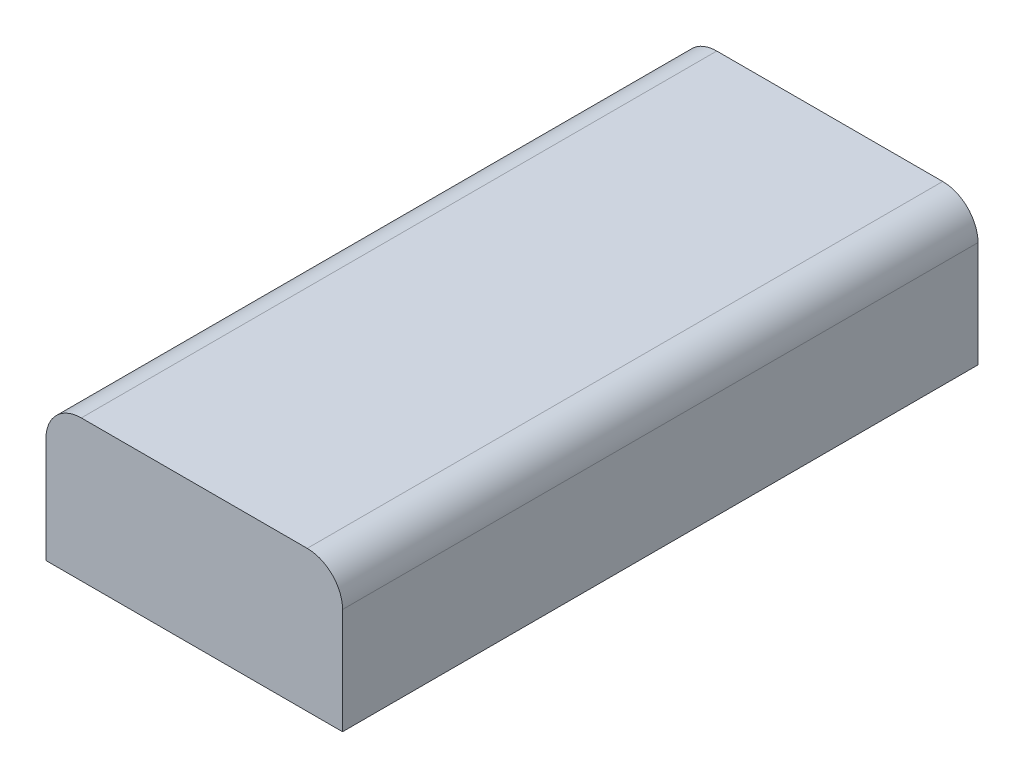
SolidWorks part; units mm, degrees
ref_plane "Alzado" through (0, 0, 0) normal (0, 0, 1) x (1, 0, 0)
ref_plane "Planta" through (0, 0, 0) normal (0, 1, 0) x (1, 0, 0)
ref_plane "Vista lateral" through (0, 0, 0) normal (1, 0, 0) x (0, 0, -1)
sketch "Croquis1" plane through (0, 0, 0) normal (0, 0, 1) x (1, 0, 0)
  line L1 (0, 0) -> (42, 0)
  line L2 (0, 0) -> (0, -20)
  line L3 (0, -20) -> (42, -20)
  line L4 (42, 0) -> (42, -20)
  dimension "D1" = 42
  dimension "D2" = 20
extrude "Saliente-Extruir1" add sketch "Croquis1" along normal blind 90
sketch "Croquis2" plane through (0, -20, 0) normal (0, -1, 0) x (1, 0, 0)
  line L0 (21, 90) -> (21, 0) construction
  line L1 (0, 90) -> (42, 90) construction
  line L2 (0, 0) -> (42, 0) construction
  line L3 (42, 45) -> (0, 45) construction
  line L4 (42, 90) -> (42, 0) construction
  line L5 (0, 90) -> (0, 0) construction
  circle A0 centre (8.5, 62) radius 1.75
  circle A1 centre (33.5, 62) radius 1.75
  circle A2 centre (33.5, 28) radius 1.75
  circle A3 centre (8.5, 28) radius 1.75
  dimension "D1" = 3.5
  dimension "D2" = 3.5
  dimension "D3" = 12.5
  dimension "D4" = 25
  dimension "D5" = 17
extrude "Cortar-Extruir1" cut sketch "Croquis2" against normal blind 3
fillet "Redondeo1" radius 5 1 edges at (42, 0, 45)
fillet "Redondeo2" radius 5 1 edges at (0, 0, 45)
